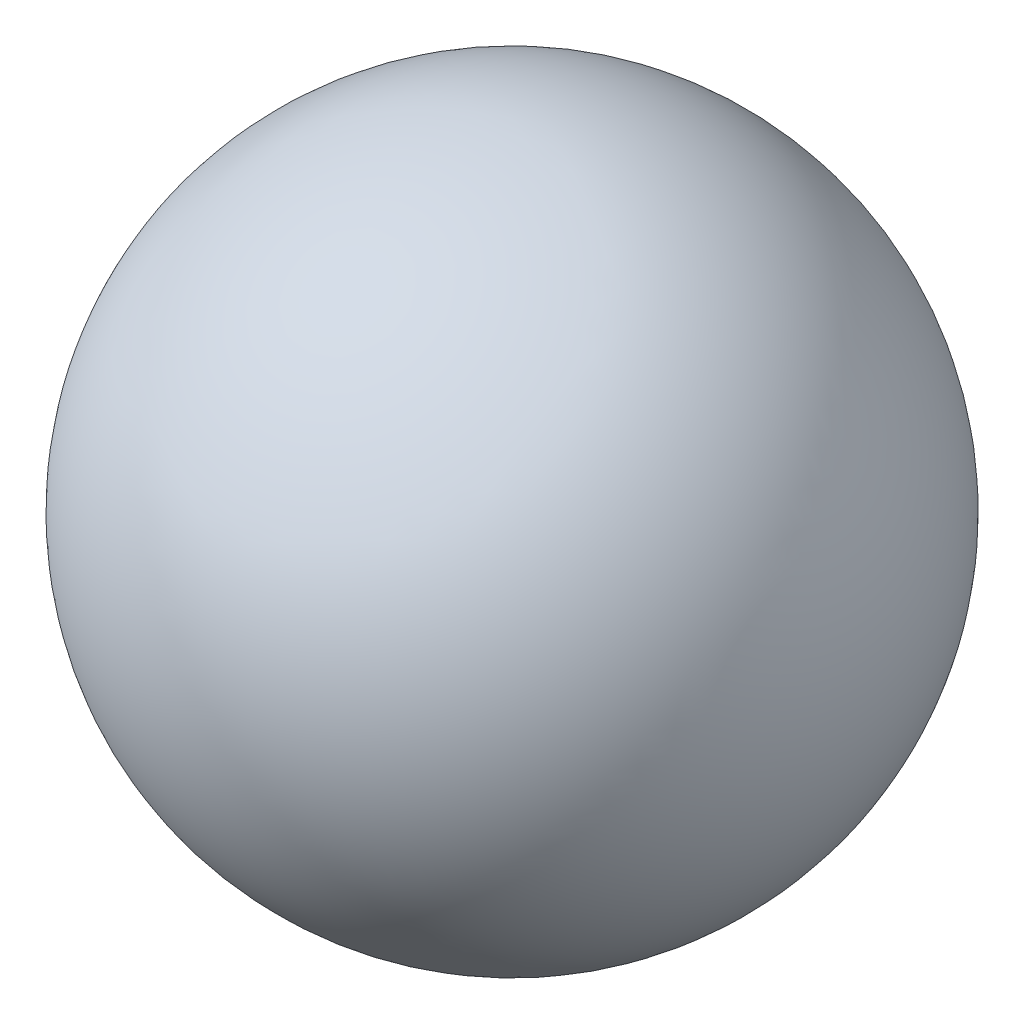
SolidWorks part; units mm, degrees
ref_plane "Спереди" through (0, 0, 0) normal (0, 0, 1) x (1, 0, 0)
ref_plane "Сверху" through (0, 0, 0) normal (0, 1, 0) x (1, 0, 0)
ref_plane "Справа" through (0, 0, 0) normal (1, 0, 0) x (0, 0, -1)
sketch "Эскиз1" plane through (0, 0, 0) normal (0, 1, 0) x (1, 0, 0)
  line L0 (-11, 0) -> (11, 0)
  line L1 (0, 22.9814) -> (0, 0) construction
  line L2 (0, 0) -> (33.1636, 0) construction
  arc A0 (-11, 0) -> (11, 0) centre (0, 0) cw
  point P7 (0, 11)
  dimension "D1" = 11
  dimension "D2" = 11
revolve "Повернуть1" add sketch "Эскиз1" angle 360 about L0
